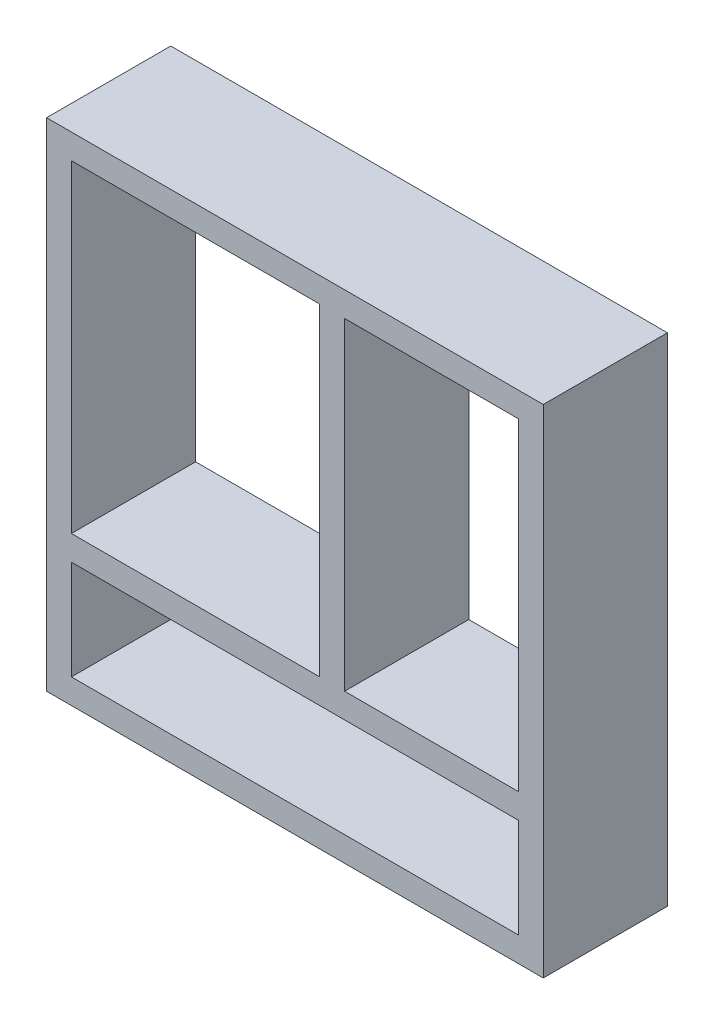
SolidWorks part; units mm, degrees
ref_plane "Front Plane" through (0, 0, 0) normal (0, 0, 1) x (1, 0, 0)
ref_plane "Top Plane" through (0, 0, 0) normal (0, 1, 0) x (1, 0, 0)
ref_plane "Right Plane" through (0, 0, 0) normal (1, 0, 0) x (0, 0, -1)
sketch "Sketch1" plane through (0, 0, 0) normal (0, 0, 1) x (1, 0, 0)
  line L1 (100, -75) -> (-100, -75)
  line L2 (100, -75) -> (100, 75)
  line L3 (100, 75) -> (-100, 75)
  line L4 (-100, -75) -> (-100, 75)
  line L5 (100, -75) -> (-100, 75) construction
  line L6 (100, 75) -> (-100, -75) construction
  line L7 (-90, -65) -> (10, -65)
  line L8 (-90, -65) -> (-90, 65)
  line L9 (-90, 65) -> (10, 65)
  line L10 (10, -65) -> (10, 65)
  line L11 (-90, -65) -> (10, 65) construction
  line L12 (-90, 65) -> (10, -65) construction
  line L13 (90, -65) -> (20, -65)
  line L14 (90, -65) -> (90, 65)
  line L15 (90, 65) -> (20, 65)
  line L16 (20, -65) -> (20, 65)
  line L17 (90, -65) -> (20, 65) construction
  line L18 (90, 65) -> (20, -65) construction
  line L23 (-100, -75) -> (-90, -75)
  line L24 (-100, -75) -> (-100, -125)
  line L25 (-100, -125) -> (-90, -125)
  line L26 (-90, -75) -> (-90, -125)
  line L27 (-100, -125) -> (100, -125)
  line L28 (-100, -125) -> (-100, -115)
  line L29 (-100, -115) -> (100, -115)
  line L30 (100, -125) -> (100, -115)
  line L31 (100, -125) -> (90, -125)
  line L32 (100, -125) -> (100, -75)
  line L33 (100, -75) -> (90, -75)
  line L34 (90, -125) -> (90, -75)
  point P0 (0, 0)
  point P6 (-40, 0)
  point P11 (55, 0)
  point P16 (55, 65)
  point P17 (15.5, 0)
  dimension "D1" = 150
  dimension "D2" = 200
  dimension "D3" = 10
  dimension "D4" = 10
  dimension "D5" = 10
  dimension "D6" = 100
  dimension "D7" = 10
  dimension "D8" = 10
  dimension "D9" = 10
  dimension "D10" = 10
  dimension "D11" = 10
  dimension "D12" = 10
  dimension "D13" = 10
  dimension "D14" = 50
extrude "Boss-Extrude1" add sketch "Sketch1" along normal blind 50 contours L24 L29 L26 L1 | L29 L24 L25 L26 | L27 L34 L29 L26 | L34 L27 L30 L29 | L34 L29 L32 L1 | L4 L1 L2 L3 L10 L7 L8 L9 L13 L16 L15 L14
